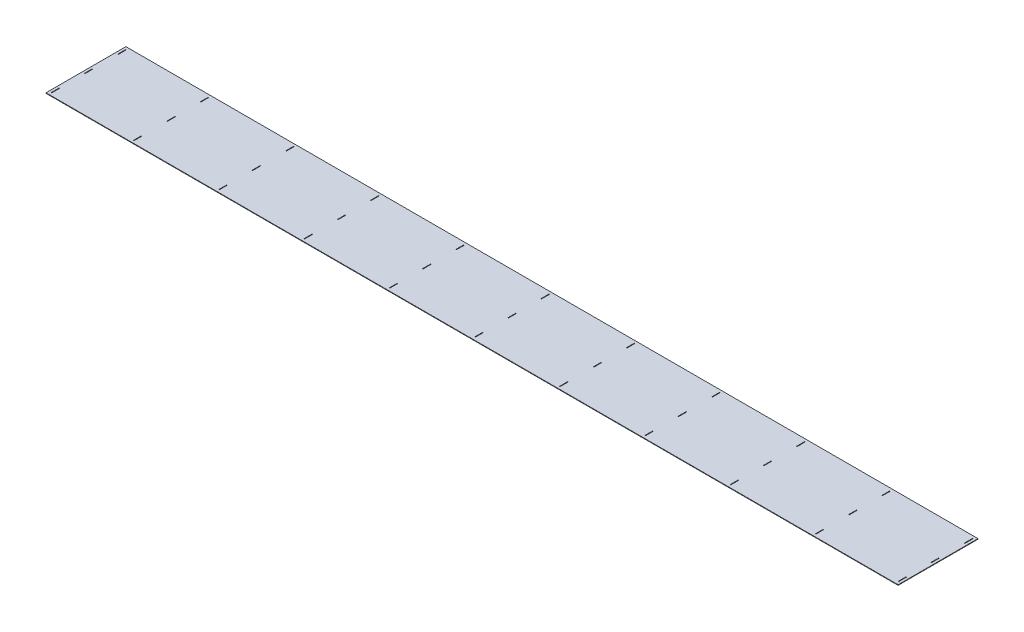
SolidWorks part; units mm, degrees
ref_plane "Front Plane" through (0, 0, 0) normal (0, 0, 1) x (1, 0, 0)
ref_plane "Top Plane" through (0, 0, 0) normal (0, 1, 0) x (1, 0, 0)
ref_plane "Right Plane" through (0, 0, 0) normal (1, 0, 0) x (0, 0, -1)
sketch "Sketch1" plane through (0, 0, 0) normal (0, 1, 0) x (1, 0, 0)
  line L0 (-800, 0) -> (800, 0) construction
  line L1 (-800, -75) -> (800, -75)
  line L2 (-800, -75) -> (-800, 75)
  line L3 (-800, 75) -> (800, 75)
  line L4 (800, -75) -> (800, 75)
  line L5 (-800, -75) -> (800, 75) construction
  line L6 (-800, 75) -> (800, -75) construction
  line L7 (-800, -70) -> (800, -70) construction
  line L8 (-795, -62.5) -> (-795, 62.5) construction
  line L9 (-794.5, 70) -> (-795.5, 70)
  line L10 (-800, 70) -> (800, 70) construction
  line L11 (-794.5, 70) -> (-794.5, 55)
  line L12 (-794.5, 55) -> (-795.5, 55)
  line L13 (-795.5, 70) -> (-795.5, 55)
  line L14 (-794.5, 70) -> (-795.5, 55) construction
  line L15 (-794.5, 55) -> (-795.5, 70) construction
  line L16 (-795.5, 7.5) -> (-794.5, 7.5)
  line L17 (-795.5, 7.5) -> (-795.5, -7.5)
  line L18 (-795.5, -7.5) -> (-794.5, -7.5)
  line L19 (-794.5, 7.5) -> (-794.5, -7.5)
  line L20 (-795.5, 7.5) -> (-794.5, -7.5) construction
  line L21 (-795.5, -7.5) -> (-794.5, 7.5) construction
  line L22 (-795.5, -55) -> (-794.5, -55)
  line L23 (-795.5, -55) -> (-795.5, -70)
  line L24 (-795.5, -70) -> (-794.5, -70)
  line L25 (-794.5, -55) -> (-794.5, -70)
  line L26 (-795.5, -55) -> (-794.5, -70) construction
  line L27 (-795.5, -70) -> (-794.5, -55) construction
  line L28 (-0.5, 70) -> (0.5, 70)
  line L29 (-0.5, 70) -> (-0.5, 55)
  line L30 (-0.5, 55) -> (0.5, 55)
  line L31 (0.5, 70) -> (0.5, 55)
  line L32 (-0.5, 70) -> (0.5, 55) construction
  line L33 (-0.5, 55) -> (0.5, 70) construction
  line L34 (-0.5, 7.5) -> (0.5, 7.5)
  line L35 (-0.5, 7.5) -> (-0.5, -7.5)
  line L36 (-0.5, -7.5) -> (0.5, -7.5)
  line L37 (0.5, 7.5) -> (0.5, -7.5)
  line L38 (-0.5, 7.5) -> (0.5, -7.5) construction
  line L39 (-0.5, -7.5) -> (0.5, 7.5) construction
  line L40 (-0.5, -55) -> (0.5, -55)
  line L41 (-0.5, -55) -> (-0.5, -70)
  line L42 (-0.5, -70) -> (0.5, -70)
  line L43 (0.5, -55) -> (0.5, -70)
  line L44 (-0.5, -55) -> (0.5, -70) construction
  line L45 (-0.5, -70) -> (0.5, -55) construction
  line L46 (-800, 55) -> (800, 55) construction
  line L47 (0, 62.5) -> (0, -62.5) construction
  line L48 (-800, 7.5) -> (800, 7.5) construction
  line L49 (795, 62.5) -> (795, -62.5) construction
  line L50 (-800, -7.5) -> (800, -7.5) construction
  line L51 (159.5, -70) -> (160.5, -70)
  line L52 (-800, -55) -> (800, -55) construction
  line L53 (794.5, 55) -> (795.5, 55)
  line L54 (794.5, 55) -> (794.5, 70)
  line L55 (794.5, 70) -> (795.5, 70)
  line L56 (795.5, 55) -> (795.5, 70)
  line L57 (794.5, 55) -> (795.5, 70) construction
  line L58 (794.5, 70) -> (795.5, 55) construction
  line L59 (794.5, -7.5) -> (795.5, -7.5)
  line L60 (794.5, -7.5) -> (794.5, 7.5)
  line L61 (794.5, 7.5) -> (795.5, 7.5)
  line L62 (795.5, -7.5) -> (795.5, 7.5)
  line L63 (794.5, -7.5) -> (795.5, 7.5) construction
  line L64 (794.5, 7.5) -> (795.5, -7.5) construction
  line L65 (794.5, -55) -> (795.5, -55)
  line L66 (794.5, -55) -> (794.5, -70)
  line L67 (794.5, -70) -> (795.5, -70)
  line L68 (795.5, -55) -> (795.5, -70)
  line L69 (794.5, -55) -> (795.5, -70) construction
  line L70 (794.5, -70) -> (795.5, -55) construction
  line L71 (159.5, -55) -> (159.5, -70)
  line L72 (160.5, -55) -> (160.5, -70)
  line L73 (159.5, -55) -> (160.5, -55)
  line L74 (160.5, 7.5) -> (160.5, -7.5)
  line L75 (159.5, 7.5) -> (160.5, 7.5)
  line L76 (159.5, 7.5) -> (159.5, -7.5)
  line L77 (159.5, -7.5) -> (160.5, -7.5)
  line L78 (159.5, 70) -> (160.5, 70)
  line L79 (159.5, 70) -> (159.5, 55)
  line L80 (160.5, 70) -> (160.5, 55)
  line L81 (159.5, 55) -> (160.5, 55)
  line L82 (319.5, -70) -> (320.5, -70)
  line L83 (319.5, -55) -> (319.5, -70)
  line L84 (320.5, -55) -> (320.5, -70)
  line L85 (319.5, -55) -> (320.5, -55)
  line L86 (320.5, 7.5) -> (320.5, -7.5)
  line L87 (319.5, 7.5) -> (320.5, 7.5)
  line L88 (319.5, 7.5) -> (319.5, -7.5)
  line L89 (319.5, -7.5) -> (320.5, -7.5)
  line L90 (319.5, 70) -> (320.5, 70)
  line L91 (319.5, 70) -> (319.5, 55)
  line L92 (320.5, 70) -> (320.5, 55)
  line L93 (319.5, 55) -> (320.5, 55)
  line L94 (479.5, -70) -> (480.5, -70)
  line L95 (479.5, -55) -> (479.5, -70)
  line L96 (480.5, -55) -> (480.5, -70)
  line L97 (479.5, -55) -> (480.5, -55)
  line L98 (480.5, 7.5) -> (480.5, -7.5)
  line L99 (479.5, 7.5) -> (480.5, 7.5)
  line L100 (479.5, 7.5) -> (479.5, -7.5)
  line L101 (479.5, -7.5) -> (480.5, -7.5)
  line L102 (479.5, 70) -> (480.5, 70)
  line L103 (479.5, 70) -> (479.5, 55)
  line L104 (480.5, 70) -> (480.5, 55)
  line L105 (479.5, 55) -> (480.5, 55)
  line L106 (639.5, -70) -> (640.5, -70)
  line L107 (639.5, -55) -> (639.5, -70)
  line L108 (640.5, -55) -> (640.5, -70)
  line L109 (639.5, -55) -> (640.5, -55)
  line L110 (640.5, 7.5) -> (640.5, -7.5)
  line L111 (639.5, 7.5) -> (640.5, 7.5)
  line L112 (639.5, 7.5) -> (639.5, -7.5)
  line L113 (639.5, -7.5) -> (640.5, -7.5)
  line L114 (639.5, 70) -> (640.5, 70)
  line L115 (639.5, 70) -> (639.5, 55)
  line L116 (640.5, 70) -> (640.5, 55)
  line L117 (639.5, 55) -> (640.5, 55)
  line L118 (-160.5, -70) -> (-159.5, -70)
  line L119 (-159.5, -55) -> (-159.5, -70)
  line L120 (-160.5, -55) -> (-160.5, -70)
  line L121 (-160.5, -55) -> (-159.5, -55)
  line L122 (-160.5, -7.5) -> (-159.5, -7.5)
  line L123 (-159.5, 7.5) -> (-159.5, -7.5)
  line L124 (-160.5, 7.5) -> (-160.5, -7.5)
  line L125 (-160.5, 7.5) -> (-159.5, 7.5)
  line L126 (-160.5, 70) -> (-159.5, 70)
  line L127 (-160.5, 70) -> (-160.5, 55)
  line L128 (-159.5, 70) -> (-159.5, 55)
  line L129 (-160.5, 55) -> (-159.5, 55)
  line L130 (-320.5, -70) -> (-319.5, -70)
  line L131 (-319.5, -55) -> (-319.5, -70)
  line L132 (-320.5, -55) -> (-320.5, -70)
  line L133 (-320.5, -55) -> (-319.5, -55)
  line L134 (-320.5, -7.5) -> (-319.5, -7.5)
  line L135 (-319.5, 7.5) -> (-319.5, -7.5)
  line L136 (-320.5, 7.5) -> (-320.5, -7.5)
  line L137 (-320.5, 7.5) -> (-319.5, 7.5)
  line L138 (-320.5, 70) -> (-319.5, 70)
  line L139 (-320.5, 70) -> (-320.5, 55)
  line L140 (-319.5, 70) -> (-319.5, 55)
  line L141 (-320.5, 55) -> (-319.5, 55)
  line L142 (-480.5, -70) -> (-479.5, -70)
  line L143 (-479.5, -55) -> (-479.5, -70)
  line L144 (-480.5, -55) -> (-480.5, -70)
  line L145 (-480.5, -55) -> (-479.5, -55)
  line L146 (-480.5, -7.5) -> (-479.5, -7.5)
  line L147 (-479.5, 7.5) -> (-479.5, -7.5)
  line L148 (-480.5, 7.5) -> (-480.5, -7.5)
  line L149 (-480.5, 7.5) -> (-479.5, 7.5)
  line L150 (-480.5, 70) -> (-479.5, 70)
  line L151 (-480.5, 70) -> (-480.5, 55)
  line L152 (-479.5, 70) -> (-479.5, 55)
  line L153 (-480.5, 55) -> (-479.5, 55)
  line L154 (-640.5, -70) -> (-639.5, -70)
  line L155 (-639.5, -55) -> (-639.5, -70)
  line L156 (-640.5, -55) -> (-640.5, -70)
  line L157 (-640.5, -55) -> (-639.5, -55)
  line L158 (-640.5, -7.5) -> (-639.5, -7.5)
  line L159 (-639.5, 7.5) -> (-639.5, -7.5)
  line L160 (-640.5, 7.5) -> (-640.5, -7.5)
  line L161 (-640.5, 7.5) -> (-639.5, 7.5)
  line L162 (-640.5, 70) -> (-639.5, 70)
  line L163 (-640.5, 70) -> (-640.5, 55)
  line L164 (-639.5, 70) -> (-639.5, 55)
  line L165 (-640.5, 55) -> (-639.5, 55)
  line L166 (-160, 70) -> (-160, 75) construction
  line L167 (160, 70) -> (160, 75) construction
  line L168 (0, 70) -> (0, 75) construction
  point P0 (0, 0)
  point P8 (-795, 62.5)
  point P17 (-795, 0)
  point P22 (-795, -62.5)
  point P27 (0, 62.5)
  point P32 (0, 0)
  point P37 (0, -62.5)
  point P54 (-795.5, 62.5)
  point P59 (795, 0)
  dimension "D1" = 150
  dimension "D2" = 1600
  dimension "D3" = 5
  dimension "D4" = 5
  dimension "D5" = 15
  dimension "D6" = 15
  dimension "D7" = 15
  dimension "D8" = 5
  dimension "D9" = 1
  dimension "D10" = 1
  dimension "D11" = 1
  dimension "D12" = 5
  dimension "D15" = 160
  dimension "D16" = 160
  dimension "D13" = 5
  dimension "D14" = 5
extrude "Boss-Extrude1" add sketch "Sketch1" along normal blind 1
